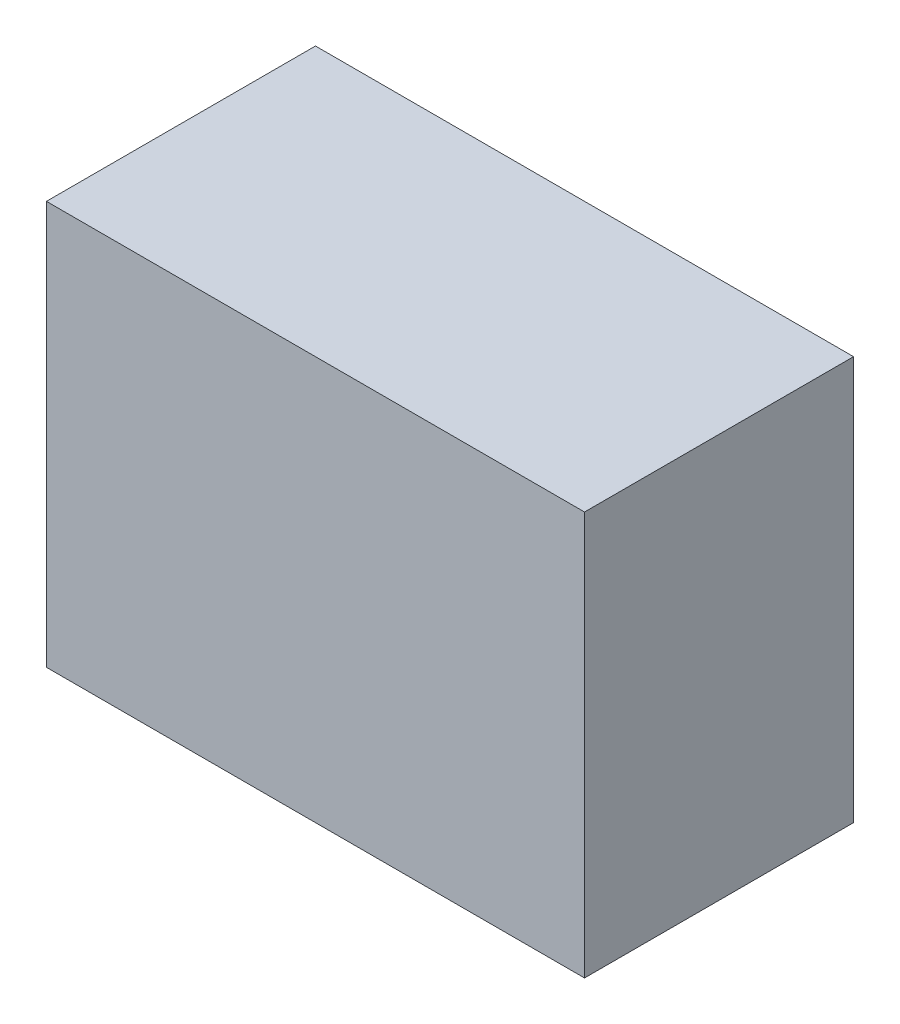
SolidWorks part; units mm, degrees
ref_plane "Front Plane" through (0, 0, 0) normal (0, 0, 1) x (1, 0, 0)
ref_plane "Top Plane" through (0, 0, 0) normal (0, 1, 0) x (1, 0, 0)
ref_plane "Right Plane" through (0, 0, 0) normal (1, 0, 0) x (0, 0, -1)
sketch "Sketch1" plane through (0, 0, 0) normal (0, 0, 1) x (1, 0, 0)
  line L1 (-10, -7.5) -> (10, -7.5)
  line L2 (-10, -7.5) -> (-10, 7.5)
  line L3 (-10, 7.5) -> (10, 7.5)
  line L4 (10, -7.5) -> (10, 7.5)
  line L5 (-10, -7.5) -> (10, 7.5) construction
  line L6 (-10, 7.5) -> (10, -7.5) construction
  point P0 (0, 0)
  dimension "D1" = 20
  dimension "D2" = 15
extrude "Boss-Extrude1" add sketch "Sketch1" along normal blind 10
